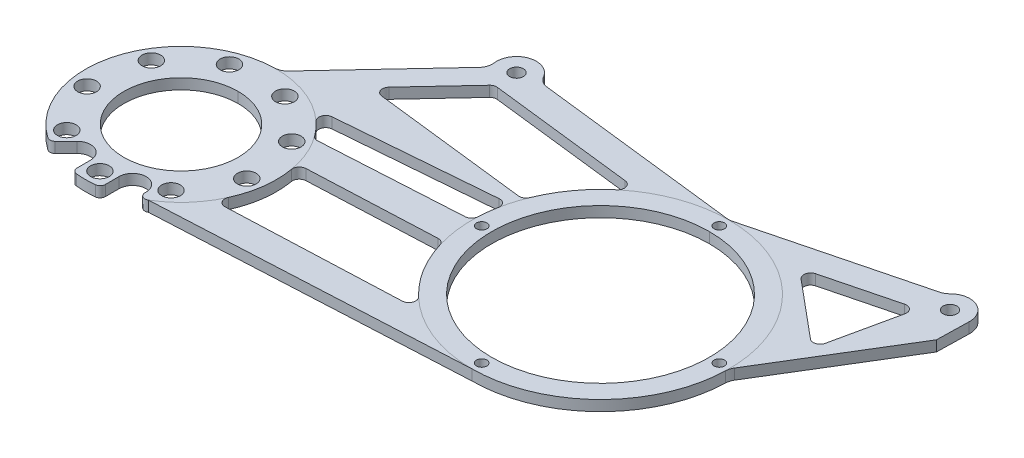
SolidWorks part; units mm, degrees
material "6061-T6 (SS)"
ref_plane "Front Plane" through (0, 0, 0) normal (0, 0, 1) x (1, 0, 0)
ref_plane "Top Plane" through (0, 0, 0) normal (0, 1, 0) x (1, 0, 0)
ref_plane "Right Plane" through (0, 0, 0) normal (1, 0, 0) x (0, 0, -1)
sketch "Sketch3" plane through (0, 0, 0) normal (0, 1, 0) x (-1, 0, 0)
  line L0 (-47.1642, 28.7869) -> (1.715, 81.0557)
  line L1 (-168.4036, 158.864) -> (-20.3196, 166.4019)
  line L2 (-251.1288, 13.883) -> (-65.1471, 22.9455)
  line L3 (-268.4562, 19.3463) -> (-265.179, 163.648)
  line L4 (-265.179, 163.648) -> (-168.4036, 158.864)
  line L8 (26.5678, 164.3167) -> (21.3029, 159.0518)
  line L9 (10.2067, 163.648) -> (10.2067, 170.2207)
  line L10 (-3.4709, 170.2207) -> (-3.4709, 163.648)
  line L11 (-16.4709, 163.648) -> (-16.4709, 164.225)
  circle A0 centre (-258.9312, 19.3463) radius 3.3
  circle A1 centre (-258.9312, 19.3463) radius 9.525
  circle A2 centre (-55.7968, 24.7614) radius 9.525
  circle A3 centre (3.3679, 127) radius 27.4955
  arc A16 (-20.3196, 166.4019) -> (29.8256, 164.5979) centre (3.3679, 127) ccw
  arc A17 (29.8256, 164.5979) -> (26.5678, 164.3167) centre (28.3638, 162.5207) ccw
  arc A18 (10.2067, 163.648) -> (21.3029, 159.0518) centre (16.7067, 163.648) ccw
  arc A19 (10.2067, 170.2207) -> (7.9181, 172.7483) centre (7.6667, 170.2207) ccw
  arc A20 (7.9181, 172.7483) -> (-1.1823, 172.7483) centre (3.3679, 127) ccw
  arc A21 (-1.1823, 172.7483) -> (-3.4709, 170.2207) centre (-0.9309, 170.2207) ccw
  arc A22 (-16.4709, 163.648) -> (-3.4709, 163.648) centre (-9.9709, 163.648) ccw
  arc A23 (-16.4709, 164.225) -> (-20.3196, 166.4019) centre (-19.0109, 164.225) ccw
  circle A26 centre (-168.4036, 96.9515) radius 61.9125
  circle A27 centre (-168.4036, 96.9515) radius 52.3875
  arc A30 (-52.5573, 25.3906) -> (-59.0363, 24.1323) centre (-55.7968, 24.7614) ccw
  arc A31 (-59.0363, 24.1323) -> (-52.5573, 25.3906) centre (-55.7968, 24.7614) ccw
  arc A32 (-47.1642, 28.7869) -> (-65.1471, 22.9455) centre (-55.7968, 24.7614) ccw
  arc A35 (-251.1288, 13.883) -> (-265.179, 26.536) centre (-258.9312, 19.3463) ccw
  circle A45 centre (-9.9709, 90.352) radius 4.5
  circle A46 centre (16.7067, 90.352) radius 4.5
  circle A47 centre (37.1429, 107.5) radius 4.5
  circle A48 centre (41.7754, 133.7723) radius 4.5
  circle A49 centre (28.4366, 156.8757) radius 4.5
  circle A50 centre (3.3679, 166) radius 4.5
  circle A51 centre (-21.7008, 156.8757) radius 4.5
  circle A52 centre (-35.0396, 133.7723) radius 4.5
  circle A53 centre (-30.4071, 107.5) radius 4.5
  circle A59 centre (-111.2536, 96.9515) radius 2.5
  circle A60 centre (-225.5536, 96.9515) radius 2.5
  circle A61 centre (-168.4036, 39.8015) radius 2.5
  arc A62 (-168.4036, 151.6015) -> (-168.4036, 156.6015) centre (-168.4036, 154.1015) ccw
  arc A63 (-168.4036, 156.6015) -> (-168.4036, 151.6015) centre (-168.4036, 154.1015) ccw
  circle A66 centre (-111.5667, 90.9777) radius 2.5
  circle A67 centre (-225.2405, 90.9777) radius 2.5
  dimension "D1" = 3.3
  dimension "D2" = 6.6
  dimension "D3" = 54.991
extrude "Boss-Extrude1" add sketch "Sketch3" along normal blind 5.08
sketch "Sketch4" plane through (0, 5.08, 0) normal (0, 1, 0) x (1, 0, 0)
  circle A0 centre (-3.3679, -127) radius 27.4955 construction
  circle A1 centre (168.4036, -96.9515) radius 52.3875 construction
  circle A2 centre (-3.3679, -127) radius 27.4955
  circle A3 centre (168.4036, -96.9515) radius 52.3875
sketch "Sketch5" plane through (0, 5.08, 0) normal (0, 1, 0) x (1, 0, 0)
  line L0 (-3.3679, -99.5045) -> (-3.3679, -154.4955)
  line L1 (-3.3679, -127) -> (-3.3679, -1127) construction
  circle A0 centre (-3.3679, -127) radius 27.4955 construction
split line "Split Line1"
sketch "Sketch6" plane through (0, 5.08, 0) normal (0, 1, 0) x (1, 0, 0)
  line L0 (168.4036, -44.564) -> (168.4036, -149.339)
  line L1 (168.4036, -96.9515) -> (168.4036, -1096.9515) construction
  circle A0 centre (168.4036, -96.9515) radius 52.3875 construction
split line "Split Line2"
sketch "Sketch7" plane through (0, 5.08, 0) normal (0, 1, 0) x (1, 0, 0)
  circle A0 centre (-3.3679, -127) radius 45.974
  arc A1 (-1.715, -81.0557) -> (-29.8256, -164.5979) centre (-3.3679, -127) ccw construction
split line "Split Line3"
sketch "Sketch8" plane through (0, 5.08, 0) normal (0, 1, 0) x (1, 0, 0)
  circle A0 centre (168.4036, -96.9515) radius 61.9125
  dimension "D1" = 123.825
split line "Split Line4"
sketch "Sketch9" plane through (0, 5.08, 0) normal (0, 1, 0) x (1, 0, 0)
  line L0 (230.3161, -96.9515) -> (268.0998, -35.0393)
  line L1 (268.4464, -19.7788) -> (265.179, -163.648) construction
  line L2 (251.1288, -13.883) -> (168.4036, -35.039)
  line L3 (168.4036, -35.039) -> (65.1471, -22.9455)
  line L4 (251.1288, -13.883) -> (65.1471, -22.9455) construction
  line L5 (251.1288, -13.883) -> (65.1471, -22.9455)
  line L7 (265.179, -163.648) -> (168.4036, -158.864) construction
  line L8 (265.179, -163.648) -> (168.4036, -158.864)
  line L9 (268.0998, -35.0393) -> (265.179, -163.648)
  circle A0 centre (168.4036, -96.9515) radius 61.9125 construction
  arc A4 (168.4036, -158.864) -> (230.3161, -96.9515) centre (168.4036, -96.9515) ccw
  point P10 (268.0998, -35.039)
extrude "Cut-Extrude1" cut sketch "Sketch9" against normal up to next
sketch "Sketch10" plane through (0, 5.08, 0) normal (0, 1, 0) x (1, 0, 0)
  line L0 (126.9644, -43.6345) -> (57.2615, -35.4708)
  line L1 (54.5358, -36.4693) -> (31.1056, -61.5244)
  line L2 (33.0824, -66.9204) -> (107.6151, -75.6497)
  line L5 (65.1471, -22.9455) -> (168.4036, -35.039) construction
  line L6 (47.1642, -28.7869) -> (-1.715, -81.0557) construction
  arc A2 (33.0824, -66.9204) -> (31.1056, -61.5244) centre (33.4568, -63.7231) cw
  arc A3 (54.5358, -36.4693) -> (57.2615, -35.4708) centre (56.887, -38.6681) cw
  arc A4 (168.4036, -35.039) -> (168.4036, -158.864) centre (168.4036, -96.9515) ccw construction
  arc A5 (128.6979, -49.4476) -> (111.0577, -73.6147) centre (168.4036, -96.9515) ccw
  arc A6 (126.9644, -43.6345) -> (128.6979, -49.4476) centre (126.5803, -46.9141) cw
  arc A7 (107.6151, -75.6497) -> (111.0577, -73.6147) centre (107.9992, -72.3701) ccw
  point P3 (123.5363, -43.0895)
  point P5 (0, 0)
  point P18 (109.8939, -76.7086)
  point P19 (135.3286, -44.6141)
  dimension "D1" = 3.302
extrude "Cut-Extrude2" cut sketch "Sketch10" against normal up to next contours L0 A3 L1 A2 L2 A7 A5 A6
sketch "Sketch11" plane through (0, 5.08, 0) normal (0, 1, 0) x (1, 0, 0)
  line L1 (105.8738, -112.6556) -> (45.0474, -115.3355)
  line L2 (123.4872, -147.4024) -> (41.5947, -150.7598)
  arc A0 (111.0577, -73.6147) -> (168.4036, -158.864) centre (168.4036, -96.9515) ccw construction
  arc A1 (109.1778, -114.9922) -> (125.633, -141.7157) centre (168.4036, -96.9515) ccw
  arc A2 (20.3196, -166.4019) -> (-1.715, -81.0557) centre (-3.3679, -127) ccw construction
  arc A3 (42.0246, -134.2891) -> (41.9387, -119.1949) centre (-3.3679, -127) ccw
  arc A5 (41.9387, -119.1949) -> (45.0474, -115.3355) centre (45.1928, -118.6343) cw
  arc A6 (105.8738, -112.6556) -> (109.1778, -114.9922) centre (106.0191, -115.9544) cw
  arc A8 (38.4556, -146.0895) -> (41.9387, -119.1949) centre (-3.3679, -127) ccw
  arc A9 (41.5947, -150.7598) -> (38.4556, -146.0895) centre (41.4595, -147.4605) cw
  arc A10 (125.633, -141.7157) -> (123.4872, -147.4024) centre (123.3519, -144.1031) cw
  point P12 (35.8473, -150.9954)
  point P13 (41.3954, -137.4814)
  point P16 (41.1465, -115.5073)
  arc M20 (-1.715, -81.0557) -> (20.3196, -166.4019) centre (-3.3679, -127) cw
  arc M22 (168.4036, -158.864) -> (111.0577, -73.6147) centre (168.4036, -96.9515) cw
  dimension "D1" = 3.302
  dimension "D2" = 3.302
sketch "Sketch12" plane through (0, 5.08, 0) normal (0, 1, 0) x (1, 0, 0)
  line L0 (249.6917, -31.7384) -> (242.8399, -63.2038)
  line L1 (237.499, -65.0374) -> (210.2259, -42.299)
  line L2 (211.5223, -36.5638) -> (245.6471, -27.8368)
  line L3 (168.4036, -35.039) -> (251.1288, -13.883) construction
  arc A0 (245.6471, -27.8368) -> (249.6917, -31.7384) centre (246.4653, -31.0358) cw
  arc A1 (210.2259, -42.299) -> (211.5223, -36.5638) centre (212.3404, -39.7628) cw
  arc A2 (237.499, -65.0374) -> (242.8399, -63.2038) centre (239.6135, -62.5012) ccw
  point P2 (0, 0)
  point P4 (255.0302, -33.3361)
  point P5 (208.037, -34.7489)
  point P6 (251.8164, -34.7489)
  dimension "D1" = 3.302
extrude "Cut-Extrude4" cut sketch "Sketch12" against normal up to next
sketch "Sketch13" plane through (0, 5.08, 0) normal (0, 1, 0) x (1, 0, 0)
  line L3 (103.4537, -97.1264) -> (36.4329, -100.9861)
  line L4 (104.0775, -81.4239) -> (29.8009, -87.5154)
  arc A1 (20.3196, -166.4019) -> (-1.715, -81.0557) centre (-3.3679, -127) ccw construction
  arc A2 (168.4036, -35.039) -> (128.6979, -49.4476) centre (168.4036, -96.9515) ccw construction
  arc A3 (33.5887, -99.6537) -> (27.83, -93.2317) centre (-3.3679, -127) ccw
  arc A4 (107.5908, -85.3344) -> (106.5621, -93.9879) centre (168.4036, -96.9515) ccw
  arc A5 (27.83, -93.2317) -> (29.8009, -87.5154) centre (30.0708, -90.8063) cw
  arc A6 (33.5887, -99.6537) -> (36.4329, -100.9861) centre (36.243, -97.6896) ccw
  arc A7 (104.0775, -81.4239) -> (107.5908, -85.3344) centre (104.3474, -84.7148) cw
  arc A8 (103.4537, -97.1264) -> (106.5621, -93.9879) centre (103.2638, -93.8299) ccw
  point P18 (106.4911, -96.9515)
  dimension "D1" = 3.302
extrude "Cut-Extrude5" cut sketch "Sketch13" against normal up to next
extrude "Cut-Extrude6" cut sketch "Sketch11" against normal up to next contours A10 A6 L1 A5 A9 L2 M22 M20
fillet "Fillet1" radius 6.604 6 edges at (251.1288, 2.54, 13.883) (230.3161, 2.54, 96.9515) (-1.715, 2.54, 81.0557) (47.1642, 2.54, 28.7869) (65.1471, 2.54, 22.9455) (168.4036, 2.54, 35.039)
